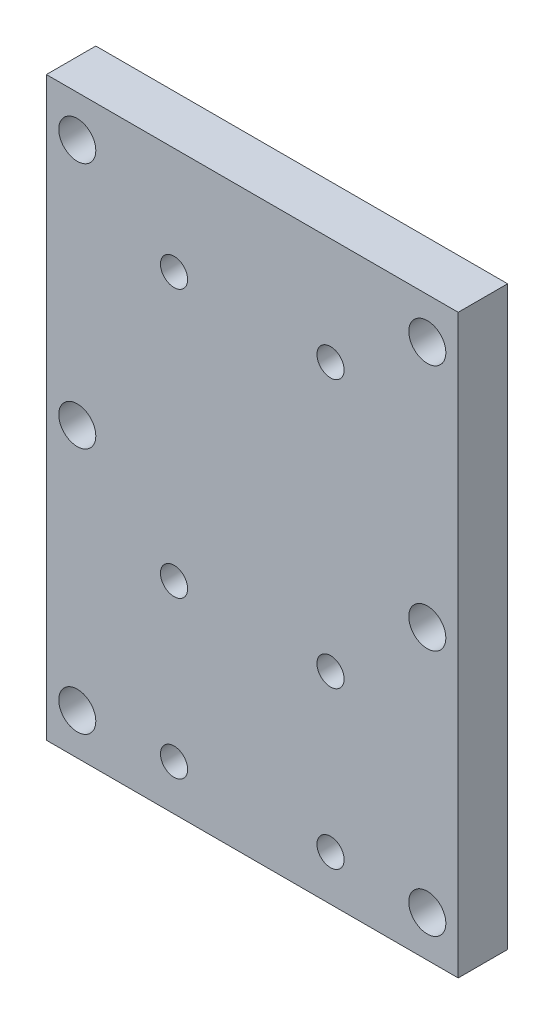
SolidWorks part; units mm, degrees
ref_plane "Front" through (0, 0, 0) normal (0, 0, 1) x (1, 0, 0)
ref_plane "Top" through (0, 0, 0) normal (0, 1, 0) x (1, 0, 0)
ref_plane "Right" through (0, 0, 0) normal (1, 0, 0) x (0, 0, -1)
sketch "草图1" plane through (0, 0, 0) normal (0, 0, 1) x (1, 0, 0)
  line L1 (-50, -70) -> (50, -70)
  line L2 (-50, -70) -> (-50, 70)
  line L3 (-50, 70) -> (50, 70)
  line L4 (50, -70) -> (50, 70)
  line L5 (-50, -70) -> (50, 70) construction
  line L6 (-50, 70) -> (50, -70) construction
  circle A0 centre (-42.5, -60) radius 4.5
  circle A1 centre (42.5, -60) radius 4.5
  circle A2 centre (42.5, 0) radius 4.5
  circle A3 centre (42.5, 60) radius 4.5
  circle A4 centre (-42.5, 0) radius 4.5
  circle A5 centre (-42.5, 60) radius 4.5
  point P0 (0, 0)
  dimension "D5" = 9
  dimension "D1" = 100
  dimension "D2" = 140
  dimension "D3" = 10
  dimension "D4" = 42.5
  dimension "D6" = 2
  dimension "D7" = 3
extrude "凸台-拉伸1" add sketch "草图1" along normal blind 12 contours L2 L3 L4 L1 | A2 | A1 | A3 | A4 | A0 | A5
hole_wizard "打孔尺寸(%根据)内六角圆柱头螺钉的类型1" positions "草图2" profile "草图3" counterbore size "M6" standard "GB" end condition through all
sketch "草图2" plane through (0, 0, 0) normal (0, 0, -1) x (-1, 0, 0)
  line L0 (50, -70) -> (-50, -70) construction
  point P0 (-19, -59)
  dimension "D1" = 11
  dimension "D2" = 19
sketch "草图3" plane through (19, -59, 0) normal (1, 0, 0) x (0, 1, 0)
  line L0 (0, 0) -> (0, 12)
  line L1 (0, 12) -> (3.3, 12)
  line L3 (3.3, 12) -> (3.3, 6.8)
  line L4 (3.3, 6.8) -> (5.5, 6.8)
  line L5 (5.5, 6.8) -> (5.5, 0)
  line L7 (5.5, 0) -> (0, 0)
  line L11 (0, -6.35) -> (0, 107.95) construction
  dimension "通孔孔直径" = 6.6
  dimension "通孔孔深度" = 12
  dimension "柱形沉头孔直径" = 11
  dimension "柱形沉头孔深度" = 6.8
pattern_linear "阵列(线性)1" count 2 spacing 38 along (0, 1, 0) count 2 spacing 38 along (-1, 0, 0) of "打孔尺寸(%根据)内六角圆柱头螺钉的类型1"
hole_wizard "打孔尺寸(%根据)内六角圆柱头螺钉的类型0" positions "草图4" profile "草图5" counterbore size "M6" standard "GB" end condition through all
sketch "草图4" plane through (0, 0, 0) normal (0, 0, -1) x (-1, 0, 0)
  circle A0 centre (-19, -21) radius 5.5 construction
  point P0 (-19, 44)
  dimension "D1" = 65
  dimension "D2" = 19
sketch "草图5" plane through (19, 44, 0) normal (1, 0, 0) x (0, 1, 0)
  line L0 (0, 0) -> (0, 12)
  line L1 (0, 12) -> (3.3, 12)
  line L3 (3.3, 12) -> (3.3, 6.8)
  line L4 (3.3, 6.8) -> (5.5, 6.8)
  line L5 (5.5, 6.8) -> (5.5, 0)
  line L7 (5.5, 0) -> (0, 0)
  line L11 (0, -6.35) -> (0, 107.95) construction
  dimension "通孔孔直径" = 6.6
  dimension "通孔孔深度" = 12
  dimension "柱形沉头孔直径" = 11
  dimension "柱形沉头孔深度" = 6.8
pattern_linear "阵列(线性)2" count 2 spacing 38 along (-1, 0, 0) of "打孔尺寸(%根据)内六角圆柱头螺钉的类型0"
